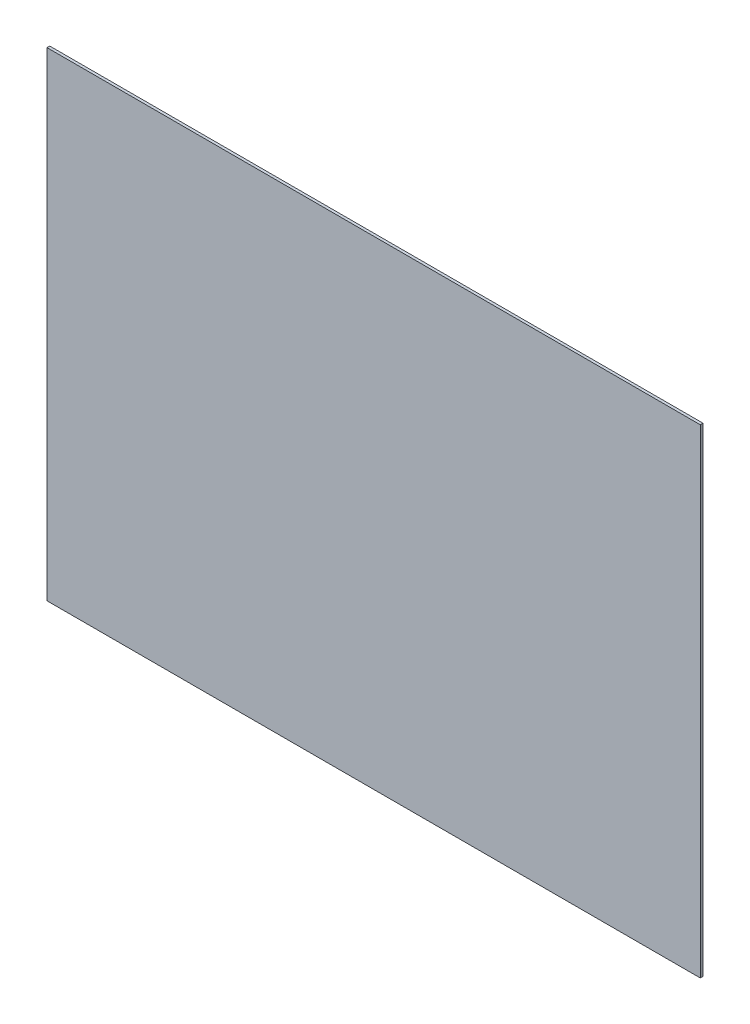
SolidWorks part; units mm, degrees
ref_plane "Front Plane" through (0, 0, 0) normal (0, 0, 1) x (1, 0, 0)
ref_plane "Top Plane" through (0, 0, 0) normal (0, 1, 0) x (1, 0, 0)
ref_plane "Right Plane" through (0, 0, 0) normal (1, 0, 0) x (0, 0, -1)
sketch "Sketch1" plane through (0, 0, 0) normal (0, 0, 1) x (1, 0, 0)
  line L1 (0, 0) -> (381, 0)
  line L2 (0, 0) -> (0, 279.4)
  line L3 (0, 279.4) -> (381, 279.4)
  line L4 (381, 0) -> (381, 279.4)
  dimension "D1" = 381
  dimension "D2" = 279.4
extrude "Boss-Extrude1" add sketch "Sketch1" along normal blind 1.5875
